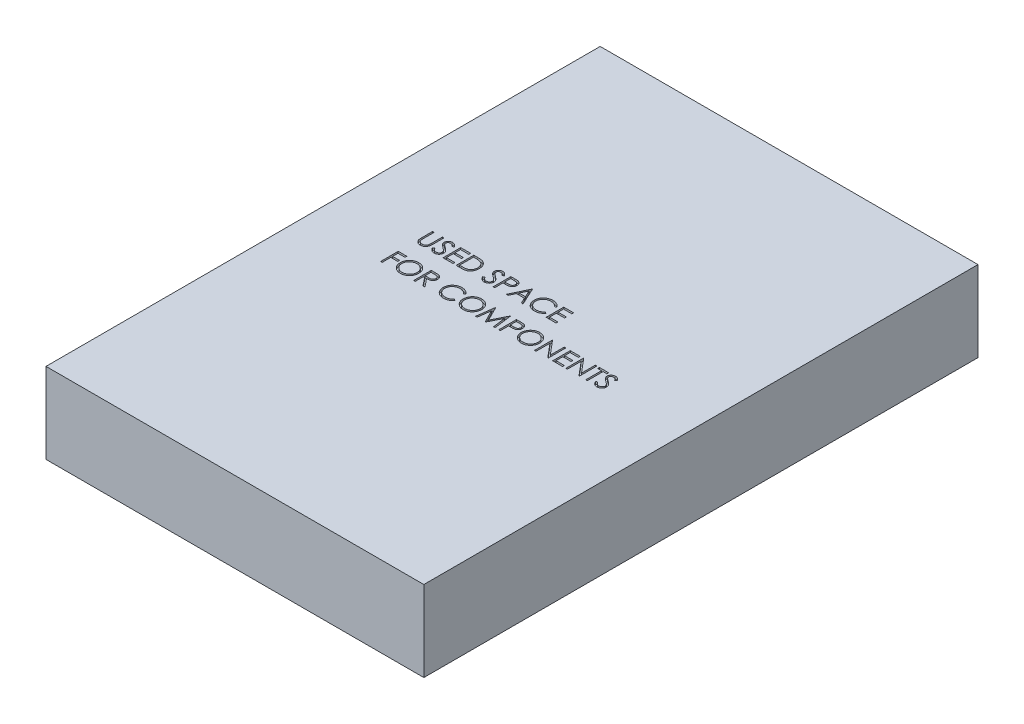
SolidWorks part; units mm, degrees
ref_plane "Front Plane" through (0, 0, 0) normal (0, 0, 1) x (1, 0, 0)
ref_plane "Top Plane" through (0, 0, 0) normal (0, 1, 0) x (1, 0, 0)
ref_plane "Right Plane" through (0, 0, 0) normal (1, 0, 0) x (0, 0, -1)
sketch "Sketch1" plane through (0, 0, 0) normal (0, 1, 0) x (1, 0, 0)
  line L1 (0, 0) -> (75, 0)
  line L2 (0, 0) -> (0, 110)
  line L3 (0, 110) -> (75, 110)
  line L4 (75, 0) -> (75, 110)
  dimension "D1" = 110
  dimension "D2" = 75
extrude "Boss-Extrude1" add sketch "Sketch1" along normal blind 16
sketch "Sketch2" plane through (0, 16, 0) normal (0, 1, 0) x (1, 0, 0)
  text T0 "USED SPACE\r\nFOR COMPONENTS"
extrude "Cut-Extrude1" cut sketch "Sketch2" against normal blind 0.5
